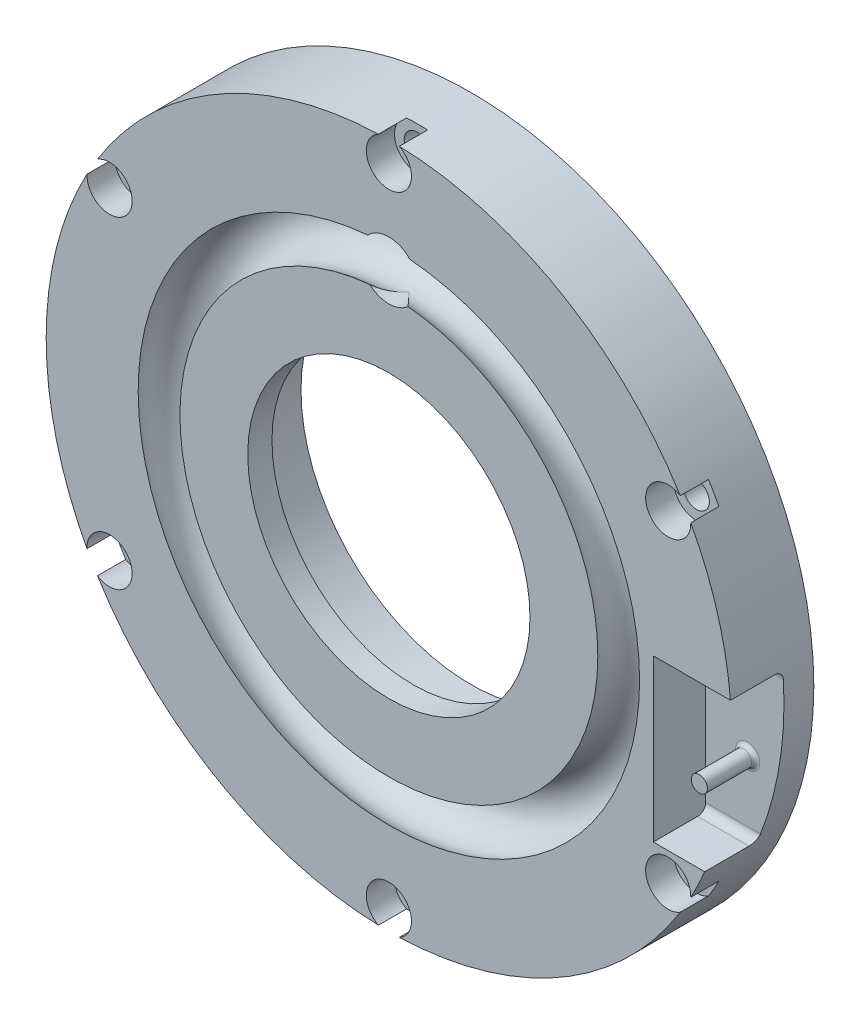
SolidWorks part; units mm, degrees
ref_plane "Front Plane" through (0, 0, 0) normal (0, 0, 1) x (1, 0, 0)
ref_plane "Top Plane" through (0, 0, 0) normal (0, 1, 0) x (1, 0, 0)
ref_plane "Right Plane" through (0, 0, 0) normal (1, 0, 0) x (0, 0, -1)
sketch "Sketch1" plane through (0, 0, 0) normal (0, 0, 1) x (1, 0, 0)
  circle A2 centre (-319.7082, 27.5786) radius 42.5
  circle A6 centre (-285.0672, 47.5786) radius 1.6
  circle A7 centre (-285.0672, 7.5786) radius 1.6
  circle A8 centre (-319.7082, -12.4214) radius 1.6
  circle A9 centre (-354.3493, 7.5786) radius 1.6
  circle A10 centre (-354.3493, 47.5786) radius 1.6
  circle A11 centre (-319.7082, 67.5786) radius 1.6
  circle A12 centre (-319.7082, 27.5786) radius 17.5
  point P19 (-319.7082, 27.5786)
  dimension "D2" = 6
extrude "Boss-Extrude1" add sketch "Sketch1" along normal blind 3
sketch "Sketch2" plane through (0, 0, 0) normal (0, 0, -1) x (-1, 0, 0)
  circle A0 centre (319.7082, 27.5786) radius 37.5
  circle A1 centre (319.7082, 27.5786) radius 21.1
  circle A3 centre (354.3493, 7.5786) radius 1.6
  circle A4 centre (354.3493, 7.5786) radius 1.6
  circle A5 centre (319.7082, -12.4214) radius 1.6
  circle A6 centre (319.7082, -12.4214) radius 1.6
  circle A7 centre (285.0672, 7.5786) radius 1.6
  circle A8 centre (285.0672, 7.5786) radius 1.6
  circle A9 centre (285.0672, 47.5786) radius 1.6
  circle A10 centre (285.0672, 47.5786) radius 1.6
  circle A11 centre (319.7082, 27.5786) radius 42.5
  circle A12 centre (319.7082, 27.5786) radius 42.5
  circle A13 centre (319.7082, 67.5786) radius 1.6
  circle A14 centre (319.7082, 67.5786) radius 1.6
  circle A15 centre (354.3493, 47.5786) radius 1.6
  circle A16 centre (354.3493, 47.5786) radius 1.6
  circle A17 centre (319.7082, 27.5786) radius 24.1
  circle M9 centre (319.7082, 27.5786) radius 42.5
  circle M10 centre (285.0672, 47.5786) radius 1.6
  circle M12 centre (285.0672, 7.5786) radius 1.6
  circle M13 centre (319.7082, -12.4214) radius 1.6
  circle M14 centre (354.3493, 7.5786) radius 1.6
  circle M15 centre (354.3493, 47.5786) radius 1.6
  circle M16 centre (319.7082, 67.5786) radius 1.6
  dimension "D9" = 3
  dimension "D1" = 5
  dimension "D2" = 0
  dimension "D3" = 0
  dimension "D4" = 0
  dimension "D5" = 0
  dimension "D6" = 0
  dimension "D7" = 0
  dimension "D8" = 0
extrude "Boss-Extrude3" add sketch "Sketch2" along normal blind 7.2 contours A17 A1 | A0 M9 M10 M12 M14 M16 M15 M13
sketch "Sketch4" plane through (0, 0, -7.2) normal (0, 0, -1) x (-1, 0, 0)
  circle A2 centre (319.7082, 27.5786) radius 37.5
  circle A3 centre (319.7082, 27.5786) radius 24.1 construction
  circle A4 centre (319.7082, 27.5786) radius 24.1
extrude "Boss-Extrude4" add sketch "Sketch4" against normal up to surface (7.2 mm away) up to face at (-302.2082, 27.5786, 0)
sketch "Sketch3" plane through (0, 0, 3) normal (0, 0, 1) x (1, 0, 0)
  circle A0 centre (-285.0672, 47.5786) radius 2.8
  circle A1 centre (-285.0672, 7.5786) radius 2.8
  circle A2 centre (-319.7082, -12.4214) radius 2.8
  circle A3 centre (-354.3493, 7.5786) radius 2.8
  circle A4 centre (-354.3493, 47.5786) radius 2.8
  circle A5 centre (-319.7082, 67.5786) radius 2.8
  point P4 (-319.7082, 27.5786)
  point P18 (-319.7082, 27.5786)
  dimension "D1" = 6
extrude "Cut-Extrude1" cut sketch "Sketch3" against normal blind 3.5
ref_plane "Plane1" through (0, 0, 0.5) normal (0, 0, 1) x (1, 0, 0)
sketch "Sketch5" plane through (0, 0, 0.5) normal (0, 0, 1) x (1, 0, 0)
  circle A2 centre (-319.7082, 27.5786) radius 28.5
sweep "Cut-Sweep1" cut path "Sketch5" circular profile diameter 7.2 parameters "D3"=7.2
sketch "Sketch22" plane through (0, 0, 3) normal (0, 0, 1) x (1, 0, 0)
  circle A2 centre (-319.7082, 56.0786) radius 3.6
extrude "Cut-Extrude2" cut sketch "Sketch22" against normal up to surface (6.0929 mm away)
sketch "Sketch23" plane through (0, 0, -7.2) normal (0, 0, -1) x (-1, 0, 0)
  circle A0 centre (319.7082, 27.5786) radius 42.5 construction
  circle A1 centre (319.7082, 27.5786) radius 42.5
  circle A2 centre (319.7082, 27.5786) radius 37.5
  circle A5 centre (319.7082, 27.5786) radius 24.1
  dimension "D1" = 5
extrude "Cut-Extrude3" cut sketch "Sketch23" against normal blind 3 contours A2 A5
fillet "Fillet1" radius 1.5 2 edges at (-357.2082, 27.5786, -4.2) (-343.8082, 27.5786, -4.2)
sketch "Sketch24" plane through (0, 0, 3) normal (0, 0, 1) x (1, 0, 0)
  line L1 (-286.9147, 31.0786) -> (-286.9147, 12.5786)
  line L5 (-286.9147, 31.0786) -> (-277.3526, 31.0786)
  line L6 (-286.9147, 12.5786) -> (-286.9147, 11.0786)
  line L7 (-286.9147, 11.0786) -> (-280.5419, 11.0786)
  arc A0 (-282.2696, 7.4641) -> (-282.2696, 47.6932) centre (-319.7082, 27.5786) ccw construction
  arc A4 (-280.5419, 11.0786) -> (-277.3526, 31.0786) centre (-319.7082, 27.5786) ccw
  point P9 (-286.9147, 21.8286)
extrude "Cut-Extrude4" cut sketch "Sketch24" against normal blind 6.5
sketch "Sketch26" plane through (0, 0, -3.5) normal (0, 0, 1) x (1, 0, 0)
  circle A0 centre (-281.7109, 19.6786) radius 1
extrude "Boss-Extrude6" add sketch "Sketch26" along normal blind 6
fillet "Fillet2" radius 0.5 1 edges at (-280.7109, 19.6786, -3.5)
fillet "Fillet3" radius 1 2 edges at (-282.1336, 31.0786, -3.5) (-283.7283, 11.0786, -3.5)
